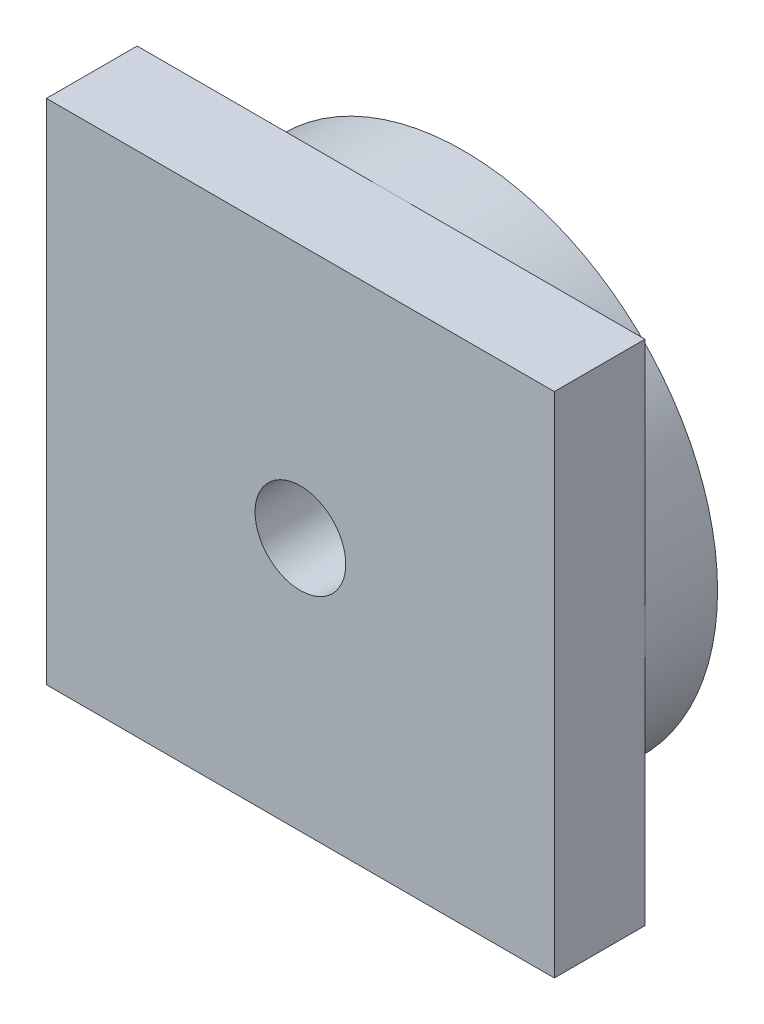
SolidWorks part; units mm, degrees
ref_plane "Ön Düzlem" through (0, 0, 0) normal (0, 0, 1) x (1, 0, 0)
ref_plane "Üst Düzlem" through (0, 0, 0) normal (0, 1, 0) x (1, 0, 0)
ref_plane "Sağ Düzlem" through (0, 0, 0) normal (1, 0, 0) x (0, 0, -1)
sketch "Sketch1" plane through (0, 0, 0) normal (0, 0, 1) x (1, 0, 0)
  circle A0 centre (0, 0) radius 18
  circle A1 centre (0, 0) radius 28
  dimension "D1" = 36
  dimension "D2" = 10
extrude "Boss-Extrude1" add sketch "Sketch1" along normal blind 22
sketch "Sketch2" plane through (0, 0, 22) normal (0, 0, 1) x (1, 0, 0)
  line L1 (-28, -28) -> (28, -28)
  line L2 (-28, -28) -> (-28, 28)
  line L3 (-28, 28) -> (28, 28)
  line L4 (28, -28) -> (28, 28)
  line L5 (-28, -28) -> (28, 28) construction
  line L6 (-28, 28) -> (28, -28) construction
  point P0 (0, 0)
  dimension "D1" = 56
  dimension "D2" = 56
extrude "Boss-Extrude2" add sketch "Sketch2" along normal blind 10
sketch "Sketch3" plane through (0, 0, 0) normal (0, 0, -1) x (-1, 0, 0)
  line L1 (-28, -28) -> (-28, 0) construction
  line L3 (28, -28) -> (-28, -28)
  line L4 (-28, -28) -> (-28, 32.0958)
  line L5 (-28, 32.0958) -> (28, 32.0958)
  line L6 (28, 32.0958) -> (28, -28)
extrude "Cut-Extrude1" cut sketch "Sketch3" against normal blind 14
sketch "Sketch4" plane through (0, 0, 22) normal (0, 0, -1) x (-1, 0, 0)
  circle A0 centre (0, 0) radius 5
  dimension "D1" = 10
extrude "Cut-Extrude2" cut sketch "Sketch4" against normal blind 14
sketch "Sketch5" plane through (0, 0, 22) normal (0, 0, -1) x (-1, 0, 0)
  circle A0 centre (0, 0) radius 21.225
  circle A1 centre (0, 0) radius 11
  dimension "D1" = 22
extrude "Boss-Extrude3" add sketch "Sketch5" along normal blind 8
